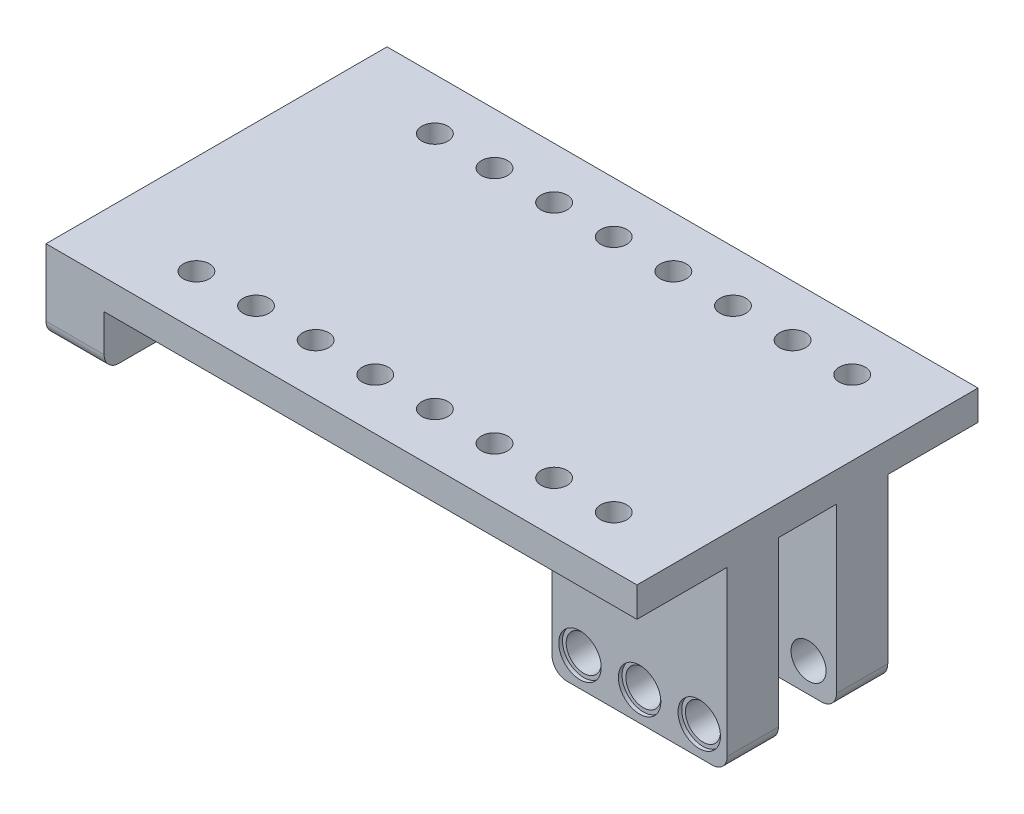
SolidWorks part; units mm, degrees
ref_plane "Спереди" through (0, 0, 0) normal (0, 0, 1) x (1, 0, 0)
ref_plane "Сверху" through (0, 0, 0) normal (0, 1, 0) x (1, 0, 0)
ref_plane "Справа" through (0, 0, 0) normal (1, 0, 0) x (0, 0, -1)
other "Configuration Table"
sketch "Эскиз1" plane through (0, 0, 0) normal (0, 1, 0) x (1, 0, 0)
  line L1 (-39.65, -22.88) -> (39.65, -22.88)
  line L2 (-39.65, -22.88) -> (-39.65, 22.88)
  line L3 (-39.65, 22.88) -> (39.65, 22.88)
  line L4 (39.65, -22.88) -> (39.65, 22.88)
  line L5 (-39.65, -22.88) -> (39.65, 22.88) construction
  line L6 (-39.65, 22.88) -> (39.65, -22.88) construction
  point P0 (0, 0)
  dimension "D1" = 79.3
  dimension "D2" = 45.76
extrude "Бобышка-Вытянуть1" add sketch "Эскиз1" along normal blind 4
sketch "Эскиз2" plane through (0, 0, 0) normal (0, -1, 0) x (1, 0, 0)
  line L0 (39.65, -22.88) -> (-39.65, -22.88) construction
  line L1 (-39.65, 22.88) -> (-31.85, 22.88)
  line L2 (-39.65, 22.88) -> (-39.65, -22.88)
  line L3 (-39.65, -22.88) -> (-31.85, -22.88)
  line L4 (-31.85, 22.88) -> (-31.85, -22.88)
  line L5 (-39.65, 22.88) -> (-31.85, -22.88) construction
  line L6 (-39.65, -22.88) -> (-31.85, 22.88) construction
  point P4 (-35.75, 0)
  dimension "D1" = 7.8
extrude "Бобышка-Вытянуть2" add sketch "Эскиз2" along normal blind 7
sketch "Эскиз3" plane through (-39.65, 0, 0) normal (-1, 0, 0) x (0, 0, 1)
  line L0 (0, 16.8114) -> (0, -18.2933) construction
  line L1 (-21.263, 0) -> (24.333, 0) construction
  line L2 (-22.88, 4) -> (22.88, 4) construction
  line L3 (-22.88, 0) -> (22.88, -7) construction
  line L4 (-22.88, 4) -> (-22.88, -7) construction
  line L5 (-8, 7.0824) -> (-8, -12.8615) construction
  line L6 (0, -3.5) -> (22.88, -3.5) construction
  line L7 (22.88, 4) -> (22.88, -7) construction
  line L8 (0, -3.5) -> (-22.88, -3.5) construction
  line L9 (8, 7.0824) -> (8, -12.6744) construction
  circle A0 centre (0, -3.5) radius 2.35
  circle A1 centre (-8, -3.5) radius 2.35
  circle A2 centre (8, -3.5) radius 2.35
  dimension "D2" = 4.7
  dimension "D1" = 4
  dimension "D3" = 8
  dimension "D4" = 8
extrude "Вырез-Вытянуть1" cut sketch "Эскиз3" against normal up to next
sketch "Эскиз4" plane through (-39.65, 0, 0) normal (-1, 0, 0) x (0, 0, 1)
  circle A0 centre (-8, -3.5) radius 2.85
  circle A1 centre (0, -3.5) radius 2.85
  circle A2 centre (8, -3.5) radius 2.85
  dimension "D1" = 5.7
extrude "Вырез-Вытянуть2" cut sketch "Эскиз4" against normal blind 0.5
sketch "Эскиз5" plane through (-31.85, 0, 0) normal (1, 0, 0) x (0, 0, -1)
  circle A0 centre (-8, -3.5) radius 2.85
  circle A1 centre (0, -3.5) radius 2.85
  circle A2 centre (8, -3.5) radius 2.85
  dimension "D1" = 5.7
extrude "Вырез-Вытянуть3" cut sketch "Эскиз5" against normal blind 0.5
sketch "Эскиз6" plane through (0, 0, 0) normal (0, -1, 0) x (1, 0, 0)
  line L0 (-42.9305, 0) -> (46.6178, 0) construction
  line L1 (16.15, 25.5476) -> (16.15, -33.4968) construction
  line L2 (39.65, 22.88) -> (39.65, -22.88) construction
  line L3 (27.8941, 22.6744) -> (27.8941, -33.4968) construction
  line L5 (16.1381, -3.9) -> (39.65, -3.9) construction
  line L6 (16.1381, -3.9) -> (16.1381, 3.9) construction
  line L7 (16.1381, 3.9) -> (39.65, 3.9) construction
  line L8 (39.65, -3.9) -> (39.65, 3.9) construction
  line L9 (16.1381, -3.9) -> (39.65, 3.9) construction
  line L10 (16.1381, 3.9) -> (39.65, -3.9) construction
  line L11 (16.1381, 3.9) -> (39.65, 3.9)
  line L12 (16.1381, 3.9) -> (16.1381, 10.7713)
  line L13 (16.1381, 10.7713) -> (39.65, 10.7713)
  line L14 (39.65, 3.9) -> (39.65, 10.7713)
  line L15 (16.1381, 3.9) -> (39.65, 10.7713) construction
  line L16 (16.1381, 10.7713) -> (39.65, 3.9) construction
  line L17 (16.1381, -3.9) -> (39.65, -3.9)
  line L18 (16.1381, -3.9) -> (16.1381, -10.7713)
  line L19 (16.1381, -10.7713) -> (39.65, -10.7713)
  line L20 (39.65, -3.9) -> (39.65, -10.7713)
  line L21 (16.1381, -3.9) -> (39.65, -10.7713) construction
  line L22 (16.1381, -10.7713) -> (39.65, -3.9) construction
  point P9 (27.8941, 0)
  point P10 (16.15, 0)
  point P11 (39.65, 0)
  point P12 (27.8941, 0)
  point P19 (27.8941, 7.3356)
  point P22 (27.8941, -7.3356)
  dimension "D1" = 23.5
  dimension "D2" = 7.8
extrude "Бобышка-Вытянуть4" add sketch "Эскиз6" along normal blind 24
sketch "Эскиз7" plane through (0, 0, -10.7713) normal (0, 0, -1) x (-1, 0, 0)
  line L0 (-16.1381, -24) -> (-39.65, -24) construction
  line L1 (-39.65, -24) -> (-16.1381, -24) construction
  line L2 (-39.65, -24) -> (-39.65, -16.2) construction
  line L3 (-39.65, -16.2) -> (-16.1381, -16.2) construction
  line L4 (-16.1381, -24) -> (-16.1381, -16.2) construction
  line L5 (-39.65, -24) -> (-16.1381, -16.2) construction
  line L6 (-39.65, -16.2) -> (-16.1381, -24) construction
  line L7 (-39.65, -24) -> (-39.65, 0) construction
  line L8 (-16.1381, -24) -> (-16.1381, 0) construction
  line L9 (-39.65, -20.1) -> (-16.1381, -20.1) construction
  circle A0 centre (-27.8941, -20.1) radius 2.35
  circle A1 centre (-19.8941, -20.1) radius 2.35
  circle A2 centre (-35.8941, -20.1) radius 2.35
  point P4 (-27.8941, -20.1)
  dimension "D3" = 4.7
  dimension "D1" = 8
  dimension "D2" = 8
  dimension "D4" = 7.8
extrude "Вырез-Вытянуть4" cut sketch "Эскиз7" against normal through all
sketch "Эскиз8" plane through (0, 0, 10.7713) normal (0, 0, 1) x (1, 0, 0)
  circle A0 centre (19.8941, -20.1) radius 2.85
  circle A1 centre (27.8941, -20.1) radius 2.85
  circle A2 centre (35.8941, -20.1) radius 2.85
  dimension "D1" = 5.7
extrude "Вырез-Вытянуть5" cut sketch "Эскиз8" against normal blind 0.5
sketch "Эскиз9" plane through (0, 0, -10.7713) normal (0, 0, -1) x (-1, 0, 0)
  circle A0 centre (-35.8941, -20.1) radius 2.85
  circle A1 centre (-27.8941, -20.1) radius 2.85
  circle A2 centre (-19.8941, -20.1) radius 2.85
  dimension "D1" = 5.7
extrude "Вырез-Вытянуть6" cut sketch "Эскиз9" against normal blind 0.5
fillet "Скругление1" radius 2 2 edges at (39.65, -24, -7.3356) (16.1381, -24, -7.3356)
fillet "Скругление2" radius 2 2 edges at (39.65, -24, 7.3356) (16.1381, -24, 7.3356)
fillet "Скругление3" radius 2 2 edges at (-35.75, -7, 22.88) (-35.75, -7, -22.88)
sketch "Эскиз10" plane through (0, 4, 0) normal (0, 1, 0) x (1, 0, 0)
  line L0 (39.65, 22.88) -> (-39.65, 22.88) construction
  line L1 (-57.1713, 0) -> (58.8892, 0) construction
  line L2 (-53.3891, 16) -> (63.0455, 16) construction
  line L3 (-52.4466, -16) -> (63.0455, -16) construction
  line L4 (29.65, 22.88) -> (29.65, -22.88) construction
  line L5 (-39.65, -22.88) -> (39.65, -22.88) construction
  line L6 (39.65, -22.88) -> (39.65, 22.88) construction
  circle A0 centre (29.65, 16) radius 1.75
  circle A1 centre (29.65, -16) radius 1.75
  circle A2 centre (21.65, 16) radius 1.75
  circle A3 centre (21.65, -16) radius 1.75
  circle A4 centre (13.65, 16) radius 1.75
  circle A5 centre (13.65, -16) radius 1.75
  circle A6 centre (5.65, 16) radius 1.75
  circle A7 centre (5.65, -16) radius 1.75
  circle A8 centre (-2.35, 16) radius 1.75
  circle A9 centre (-2.35, -16) radius 1.75
  circle A10 centre (-10.35, 16) radius 1.75
  circle A11 centre (-10.35, -16) radius 1.75
  circle A12 centre (-18.35, 16) radius 1.75
  circle A13 centre (-18.35, -16) radius 1.75
  circle A14 centre (-26.35, 16) radius 1.75
  circle A15 centre (-26.35, -16) radius 1.75
  dimension "D1" = 16
  dimension "D4" = 3.5
  dimension "D2" = 16
  dimension "D3" = 10
extrude "Вырез-Вытянуть7" cut sketch "Эскиз10" against normal blind 4
